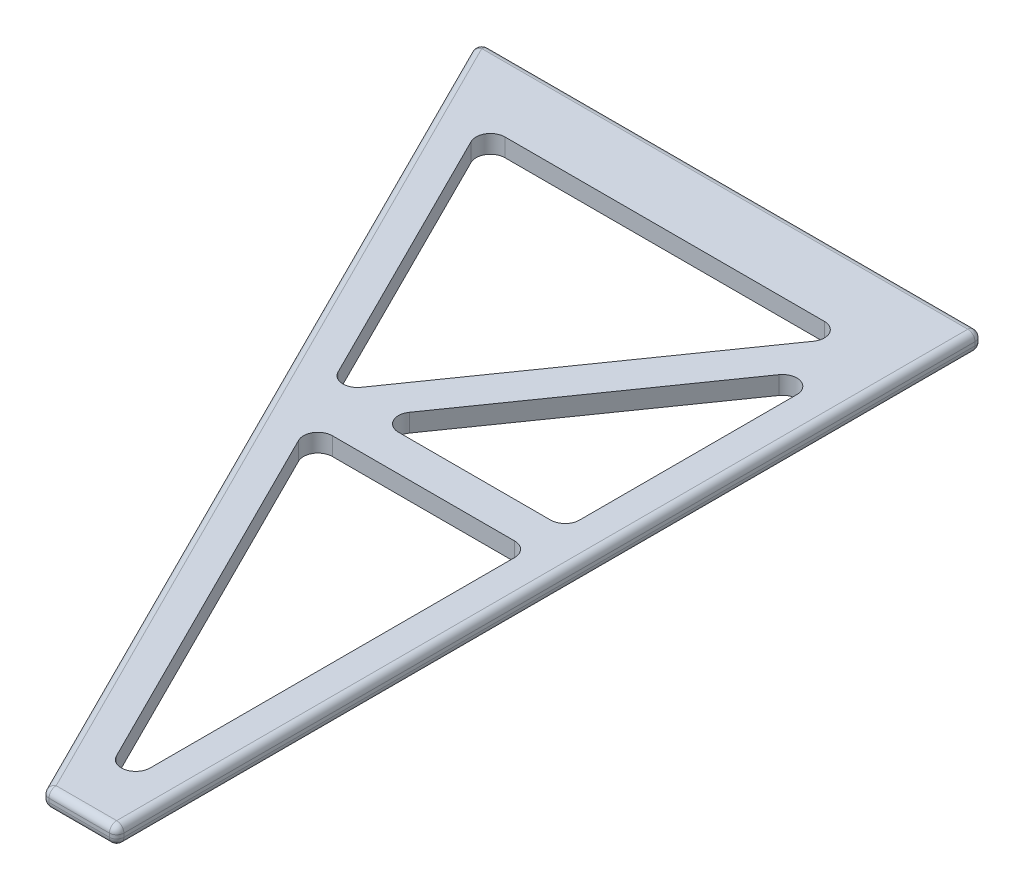
SolidWorks part; units mm, degrees
other "Markup1"
sketch "Sketch6" plane through (-76.2, 0, 0) normal (0.4646, -0.8816, -0.0837) x (0.8814, 0.4695, -0.0527)
material "Teak"
ref_plane "Front" through (0, 0, 0) normal (0, 0, 1) x (1, 0, 0)
ref_plane "Top" through (0, 0, 0) normal (0, 1, 0) x (1, 0, 0)
ref_plane "Right" through (0, 0, 0) normal (1, 0, 0) x (0, 0, -1)
sketch "Sketch1" plane through (0, 0, 0) normal (0, 0, 1) x (1, 0, 0)
  line L1 (0, 0) -> (-254, 0)
  line L2 (0, 0) -> (0, 6.35)
  line L3 (0, 6.35) -> (-254, 6.35)
  line L4 (-254, 0) -> (-254, 6.35)
  dimension "D1" = 6.35
  dimension "D2" = 254
extrude "Boss-Extrude1" add sketch "Sketch1" along normal blind 304.8 contours L3 L4 L1 L2
sketch "Sketch2" plane through (0, 6.35, 0) normal (0, 1, 0) x (1, 0, 0)
  line L0 (-254, 0) -> (-101.6, -304.8)
  line L1 (0, -304.8) -> (-254, -304.8) construction
  line L2 (0, -304.8) -> (-254, -304.8)
  line L3 (0, -304.8) -> (-254, -304.8)
  line L4 (-254, -304.8) -> (-254, 0)
  line L5 (-254, -304.8) -> (-254, 0)
  line L6 (-254, 0) -> (0, 0)
  line L7 (-254, 0) -> (0, 0)
  line L8 (0, 0) -> (0, -304.8)
  line L9 (0, 0) -> (0, -304.8)
  line M2 (-254, 0) -> (-254, -304.8)
  line M3 (-254, -304.8) -> (0, -304.8)
  dimension "D1" = 101.6
extrude "Cut-Extrude1" cut sketch "Sketch2" against normal blind 304.8 contours L0 M2 M3
sketch "Sketch4" plane through (0, 6.35, 0) normal (0, 1, 0) x (1, 0, 0)
  line L0 (0, -304.8) -> (-101.6, -304.8) construction
  line L1 (-76.2, 0) -> (-257.808, 0)
  line L5 (-76.2, -127) -> (-76.2, 0)
  line L7 (-76.2, -304.8) -> (-76.2, -177.8)
  line L8 (-76.2, 0) -> (29.5686, 0)
  line L11 (0, 0) -> (-254, 0) construction
  line L12 (-76.2, -177.8) -> (-76.2, -304.8)
  line L17 (-76.2, -304.8) -> (0, -304.8)
  line L18 (0, -304.8) -> (0, 0)
  line L19 (0, 0) -> (-76.2, 0)
  line L26 (-76.2, -177.8) -> (-76.2, -127)
  point P5 (0, -152.4)
  dimension "D1" = 76.2
  dimension "D2" = 25.4
  dimension "D5" = 76.2
extrude "Cut-Extrude2" cut sketch "Sketch4" against normal through all
sketch "Sketch9" plane through (0, 6.35, 0) normal (0, 1, 0) x (1, 0, 0)
  line L0 (-165.1, 0) -> (-165.1, -25.4) construction
  line L1 (-76.2, 0) -> (-254, 0) construction
  line L2 (-165.1, -25.4) -> (-96.6519, -25.4) construction
  line L3 (-76.2, -128.6138) -> (-88.9, -128.6138) construction
  line L4 (-76.2, -304.8) -> (-76.2, 0) construction
  line L5 (-88.9, 1077.8138) -> (-88.9, -25.4) construction
  line L6 (-177.8, -152.4) -> (-166.4408, -146.7204) construction
  line L7 (-254, 0) -> (-101.6, -304.8) construction
  line L8 (280.7728, -1041.1476) -> (-166.3522, -146.8976) construction
  line L9 (-88.9, -25.4) -> (948.1282, -25.4) construction
  line L10 (-88.9, -36.4709) -> (-88.9, -134.1976) construction
  line L11 (-102.2492, -33.3938) -> (-167.8653, -127.1033)
  line L12 (-158.1326, -146.8976) -> (-93.98, -146.8976)
  line L13 (-98.1413, -49.6688) -> (-151.7317, -126.2038)
  line L14 (-147.5704, -134.1976) -> (-93.98, -134.1976)
  line L15 (-223.425, -32.7518) -> (-176.5703, -126.4613)
  line L16 (-88.9, -280.2827) -> (-88.9, -151.9776)
  line L17 (-218.8814, -25.4) -> (-106.4105, -25.4)
  line L18 (-88.9, -146.8976) -> (-88.9, -222.5911) construction
  line L19 (-88.9, -129.1176) -> (-88.9, -52.5826)
  line L20 (-172.7566, -134.0887) -> (-210.9843, -57.6333) construction
  line L21 (-162.6763, -154.2494) -> (-98.5237, -282.5546)
  arc A0 (-162.6763, -154.2494) -> (-158.1326, -146.8976) centre (-158.1326, -151.9776) cw
  arc A1 (-98.5237, -282.5546) -> (-88.9, -280.2827) centre (-93.98, -280.2827) ccw
  arc A2 (-93.98, -146.8976) -> (-88.9, -151.9776) centre (-93.98, -151.9776) cw
  arc A3 (-223.425, -32.7518) -> (-218.8814, -25.4) centre (-218.8814, -30.48) cw
  arc A4 (-102.2492, -33.3938) -> (-106.4105, -25.4) centre (-106.4105, -30.48) ccw
  arc A5 (-98.1413, -49.6688) -> (-88.9, -52.5826) centre (-93.98, -52.5826) cw
  arc A6 (-93.98, -134.1976) -> (-88.9, -129.1176) centre (-93.98, -129.1176) ccw
  arc A7 (-151.7317, -126.2038) -> (-147.5704, -134.1976) centre (-147.5704, -129.1176) ccw
  arc A8 (-167.8653, -127.1033) -> (-176.5703, -126.4613) centre (-172.0266, -124.1895) cw
  point P33 (-88.9, -301.8019)
  point P39 (-227.101, -25.4)
  dimension "D4" = 5.08
  dimension "D1" = 25.4
  dimension "D2" = 12.7
  dimension "D3" = 12.7
extrude "Cut-Extrude3" cut sketch "Sketch9" against normal up to next
fillet "Fillet2" radius 2.54 12 edges at (-88.9, 6.35, 304.8) (-88.9, 0, 304.8) (-101.6, 3.175, 304.8) (-177.8, 6.35, 152.4) (-177.8, 0, 152.4) (-165.1, 6.35, 0) (-165.1, 0, 0) (-254, 3.175, 0) (-76.2, 3.175, 304.8) (-76.2, 0, 152.4) (-76.2, 6.35, 152.4) (-76.2, 3.175, 0)
